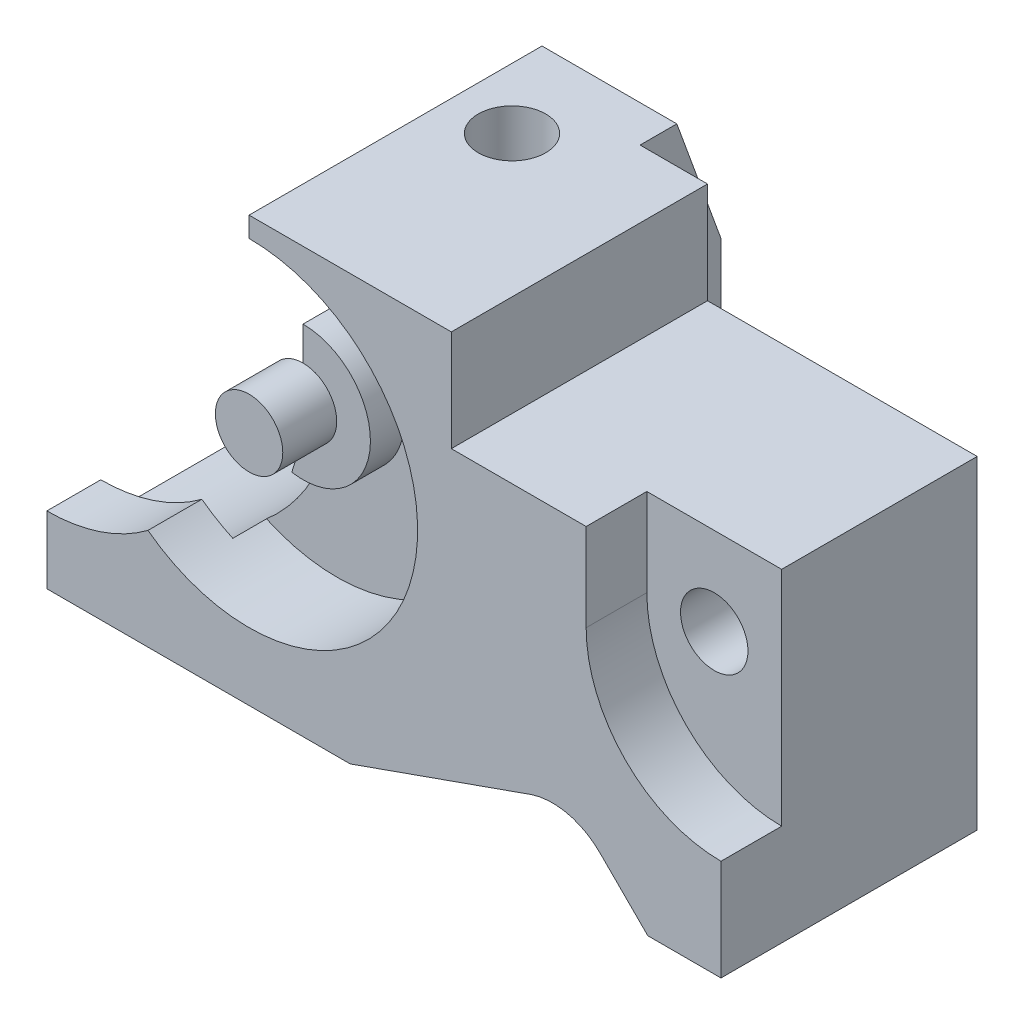
SolidWorks part; units mm, degrees
material "Copper"
ref_plane "Front Plane" through (0, 0, 0) normal (0, 0, 1) x (1, 0, 0)
ref_plane "Top Plane" through (0, 0, 0) normal (0, 1, 0) x (1, 0, 0)
ref_plane "Right Plane" through (0, 0, 0) normal (1, 0, 0) x (0, 0, -1)
sketch "Sketch1" plane through (0, 0, 0) normal (0, 0, 1) x (1, 0, 0)
  line L0 (0, 0) -> (45, 0)
  line L1 (45, 0) -> (148, 37.4889) construction
  line L2 (45, 0) -> (85, 0) construction
  line L3 (85, 0) -> (75, 0) construction
  line L4 (45, 0) -> (71.8691, 9.4972)
  line L5 (85, 0) -> (100, 0)
  line L6 (100, 0) -> (100, 48)
  line L7 (100, 48) -> (60, 48)
  line L8 (60, 48) -> (60, 63)
  line L9 (89.1421, 0) -> (82.0711, 7.0711)
  line L10 (60, 63) -> (30, 63)
  line L11 (0, 0) -> (0, 5)
  line L12 (0, 5) -> (0, 35) construction
  line L13 (30, 35) -> (30, 63)
  arc A0 (82.0711, 7.0711) -> (71.8691, 9.4972) centre (75, 0) ccw
  arc A1 (0, 5) -> (30, 35) centre (0, 35) ccw
  dimension "D1" = 45
  dimension "D2" = 20
  dimension "D3" = 40
  dimension "D4" = 10
  dimension "D5" = 15
  dimension "D6" = 48
  dimension "D7" = 40
  dimension "D8" = 15
  dimension "D9" = 45
  dimension "D10" = 5
  dimension "D11" = 30
extrude "Boss-Extrude1" add sketch "Sketch1" along normal blind 50
sketch "Sketch3" plane through (0, 0, 50) normal (0, 0, 1) x (1, 0, 0)
  line L0 (100, 0) -> (100, 48) construction
  line L1 (89.1421, 0) -> (100, 0) construction
  circle A0 centre (90, 35) radius 5
  dimension "D1" = 10
  dimension "D2" = 10
  dimension "D3" = 35
extrude "Cut-Extrude1" cut sketch "Sketch3" against normal blind 64
sketch "Sketch6" plane through (0, 0, 50) normal (0, 0, 1) x (1, 0, 0)
  line L1 (100, 48) -> (60, 48) construction
  line L3 (89.1421, 0) -> (100, 0) construction
  line L4 (80, 48) -> (100, 48)
  line L6 (100, 0) -> (100, 48) construction
  line L8 (100, 48) -> (100, 35)
  line L9 (100, 35) -> (100, 15)
  line L10 (80, 35) -> (80, 48)
  arc A1 (100, 15) -> (80, 35) centre (100, 35) cw
  dimension "D1" = 20
  dimension "D2" = 35
  dimension "D3" = 20
extrude "Cut-Extrude2" cut sketch "Sketch6" against normal blind 9
sketch "Sketch7" plane through (0, 63, 0) normal (0, 1, 0) x (1, 0, 0)
  line L0 (60, -50) -> (30, -50) construction
  line L1 (30, -50) -> (30, 0) construction
  circle A0 centre (39, -20) radius 5
  dimension "D1" = 10
  dimension "D2" = 30
  dimension "D3" = 9
extrude "Cut-Extrude3" cut sketch "Sketch7" against normal blind 82
sketch "Sketch8" plane through (0, 48, 0) normal (0, 1, 0) x (1, 0, 0)
  line L0 (60, -50) -> (60, 0) construction
  line L1 (100, 0) -> (60, 0)
  line L2 (100, 0) -> (100, -12)
  line L3 (100, -12) -> (60, -12)
  line L4 (60, 0) -> (60, -12)
  dimension "D1" = 12
extrude "Cut-Extrude4" cut sketch "Sketch8" against normal blind 82
sketch "Sketch9" plane through (0, 63, 0) normal (0, 1, 0) x (1, 0, 0)
  line L1 (60, 0) -> (50, 0)
  line L2 (60, 0) -> (60, -12)
  line L3 (60, -12) -> (50, -12)
  line L4 (50, 0) -> (50, -12)
  dimension "D1" = 12
  dimension "D2" = 10
extrude "Cut-Extrude5" cut sketch "Sketch9" against normal blind 82
sketch "Sketch10" plane through (50, 0, 0) normal (1, 0, 0) x (0, 0, -1)
  line L0 (0, 63) -> (0, 45)
  line L1 (0, 63) -> (0, 1.7673) construction
  line L2 (0, 45) -> (-6.5515, 63)
  line L3 (0, 63) -> (-12, 63) construction
  line L4 (-6.5515, 63) -> (0, 63)
  dimension "D1" = 18
  dimension "D2" = 20
extrude "Cut-Extrude6" cut sketch "Sketch10" against normal blind 82
sketch "Sketch11" plane through (0, 0, 50) normal (0, 0, 1) x (1, 0, 0)
  line L0 (30, 63) -> (30, 0) construction
  line L1 (0, 0) -> (45, 0) construction
  line L2 (100, 35) -> (30, 35) construction
  line L3 (100, 15) -> (100, 48) construction
  circle A0 centre (30, 35) radius 25
  dimension "D1" = 35
extrude "Cut-Extrude7" cut sketch "Sketch11" against normal blind 13
sketch "Sketch12" plane through (0, 0, 50) normal (0, 0, 1) x (1, 0, 0)
  line L0 (0, 5) -> (0, 10)
  line L1 (0, 10) -> (0, 35) construction
  arc A0 (0, 10) -> (15, 15) centre (0, 35) ccw
  arc A1 (19.5833, 12.2735) -> (15, 15) centre (30, 35) cw
  arc A3 (0, 5) -> (19.5833, 12.2735) centre (0, 35) ccw
  arc A4 (19.5833, 12.2735) -> (30, 60) centre (30, 35) ccw construction
  arc M4 (19.5833, 12.2735) -> (0, 5) centre (0, 35) cw
  dimension "D1" = 5
  dimension "D2" = 25
extrude "Boss-Extrude2" add sketch "Sketch12" against normal blind 8 contours A1 A0 L0 M4
sketch "Sketch13" plane through (0, 0, 37) normal (0, 0, 1) x (1, 0, 0)
  line L0 (30, 35) -> (30, 60) construction
  line L1 (30, 45) -> (30, 35)
  line L2 (0, 0) -> (0, 35) construction
  arc A0 (30, 45) -> (28.3333, 25.1399) centre (30, 35) cw
  arc A1 (19.5833, 12.2735) -> (30, 35) centre (0, 35) ccw construction
  arc A2 (28.3333, 25.1399) -> (30, 35) centre (0, 35) ccw
  line M3 (30, 60) -> (30, 35)
  arc M4 (30, 35) -> (19.5833, 12.2735) centre (0, 35) cw
  dimension "D1" = 10
  dimension "D2" = 35
extrude "Boss-Extrude3" add sketch "Sketch13" along normal blind 5 contours A0 M3 M4
sketch "Sketch14" plane through (0, 0, 42) normal (0, 0, 1) x (1, 0, 0)
  circle A0 centre (30, 35) radius 5
  dimension "D1" = 10
extrude "Boss-Extrude4" add sketch "Sketch14" along normal up to surface (8 mm away) up to face at (58.0604, 23.9499, 50)
